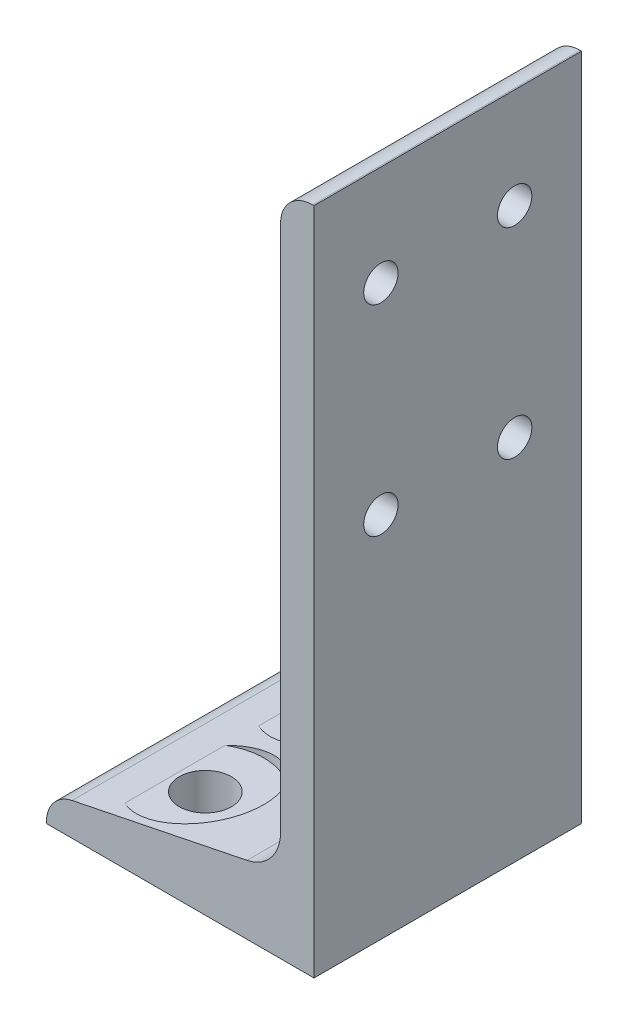
SolidWorks part; units mm, degrees
ref_plane "Front Plane" through (0, 0, 0) normal (0, 0, 1) x (1, 0, 0)
ref_plane "Top Plane" through (0, 0, 0) normal (0, 1, 0) x (1, 0, 0)
ref_plane "Right Plane" through (0, 0, 0) normal (1, 0, 0) x (0, 0, -1)
sketch "Sketch1" plane through (0, 0, 0) normal (0, 0, 1) x (1, 0, 0)
  line L0 (0, 127) -> (0, 0)
  line L1 (0, 0) -> (-50.8, 0)
  line L2 (-50.8, 0) -> (-50.8, 0.254)
  line L3 (-45.9207, 6.2273) -> (-12.7032, 12.9934)
  line L4 (-6.35, 20.7712) -> (-6.35, 120.904)
  line L5 (-0.254, 127) -> (0, 127)
  arc A0 (-12.7032, 12.9934) -> (-6.35, 20.7712) centre (-14.2875, 20.7712) ccw
  arc A1 (-50.8, 0.254) -> (-45.9207, 6.2273) centre (-44.704, 0.254) cw
  arc A2 (-6.35, 120.904) -> (-0.254, 127) centre (-0.254, 120.904) cw
  point P9 (-6.35, 14.2875)
  point P14 (-6.35, 127)
  dimension "D2" = 7.9375
  dimension "D3" = 6.096
  dimension "D1" = 14.2875
  dimension "A" = 127
  dimension "F" = 50.8
  dimension "E" = 6.35
extrude "Extrude1" add sketch "Sketch1" along normal mid plane 50.8
sketch "Sketch2" plane through (0, 0, 0) normal (1, 0, 0) x (0, 0, -1)
  line L0 (0, 0) -> (0, 69.85) construction
  line L1 (0, 69.85) -> (0, 107.95) construction
  circle A0 centre (0, 69.85) radius 3.2639
  circle A1 centre (0, 107.95) radius 3.2639
  dimension "K" = 6.5278
  dimension "B" = 69.85
  dimension "C" = 38.1
sketch "Sketch3" plane through (0, 0, 0) normal (0, 1, 0) x (1, 0, 0)
  line L0 (-50.8, 0) -> (-33.3248, 0) construction
  line L1 (-50.8, -25.4) -> (-50.8, 25.4) construction
  circle A0 centre (-33.3248, 0) radius 4.953
  dimension "L" = 9.906
  dimension "D1" = 17.4752
ref_plane "Plane1" through (0, 7.62, 0) normal (0, 1, 0) x (-1, 0, 0)
sketch "Sketch4" plane through (0, 7.62, 0) normal (0, 1, 0) x (-1, 0, 0)
  line L0 (33.3248, 11.1125) -> (50.8, 11.1125)
  line L1 (33.3248, -11.1125) -> (50.8, -11.1125)
  line L2 (50.8, 25.4) -> (50.8, -25.4) construction
  line L3 (50.8, 11.1125) -> (50.8, -11.1125)
  arc A0 (33.3248, 11.1125) -> (33.3248, -11.1125) centre (33.3248, 0) ccw
  arc A1 (33.3248, 11.1125) -> (33.3248, -11.1125) centre (33.3248, 0) cw construction
  dimension "M" = 22.225
sketch "Sketch5" [suppressed] plane through (-6.35, 0, 0) normal (-1, 0, 0) x (0, 0, 1)
  circle A0 centre (0, 69.85) radius 4.1656 construction
  circle A1 centre (0, 107.95) radius 4.1656 construction
  circle A2 centre (0, 69.85) radius 4.1656
  circle A3 centre (0, 107.95) radius 4.1656
extrude "Cut-Extrude1" [suppressed] cut sketch "Sketch5" against normal through all
sketch "Sketch6" [suppressed] plane through (0, 6.858, 0) normal (0, 1, 0) x (-1, 0, 0)
  circle A0 centre (33.3248, 0) radius 6.7437 construction
  circle A1 centre (33.3248, 0) radius 6.7437
extrude "Cut-Extrude2" [suppressed] cut sketch "Sketch6" against normal through all
sketch "Sketch7" [suppressed] plane through (0, 6.858, 0) normal (0, 1, 0) x (-1, 0, 0)
  line L3 (50.8, 14.2875) -> (33.3248, 14.2875)
  line L4 (50.8, 14.2875) -> (33.3248, 14.2875)
  line L5 (50.8, -14.2875) -> (50.8, 14.2875)
  line L6 (50.8, -14.2875) -> (50.8, 14.2875)
  line L7 (33.3248, -14.2875) -> (50.8, -14.2875)
  line L8 (33.3248, -14.2875) -> (50.8, -14.2875)
  arc A1 (33.3248, 14.2875) -> (33.3248, -14.2875) centre (33.3248, 0) ccw
  arc A2 (33.3248, 14.2875) -> (33.3248, -14.2875) centre (33.3248, 0) ccw
  dimension "D1" = 0
extrude "Cut-Extrude3" [suppressed] cut sketch "Sketch7" along normal through all
sketch "Sketch9" plane through (-6.35, 0, 0) normal (-1, 0, 0) x (0, 0, 1)
  line L0 (-12.7, 107.95) -> (12.7, 107.95) construction
  circle A0 centre (12.7, 107.95) radius 3.2639
  circle A1 centre (12.7, 69.85) radius 3.2639
  circle A2 centre (-12.7, 69.85) radius 3.2639
  circle A3 centre (-12.7, 107.95) radius 3.2639
  circle A4 centre (0, 69.85) radius 3.2639 construction
  dimension "D1" = 25.4
sketch "Sketch10" plane through (0, 0, 0) normal (0, 1, 0) x (1, 0, 0)
  line L0 (-33.3248, -12.7) -> (-33.3248, 12.7) construction
  line L1 (-50.8, -11.1125) -> (-50.8, 11.1125) construction
  line L2 (-50.8, 23.8125) -> (-33.3248, 23.8125)
  line L3 (-50.8, 23.8125) -> (-50.8, 1.5875)
  line L4 (-50.8, 1.5875) -> (-33.3248, 1.5875)
  line L6 (-50.8, -1.5875) -> (-33.3248, -1.5875)
  line L7 (-50.8, -1.5875) -> (-50.8, -23.8125)
  line L8 (-50.8, -23.8125) -> (-33.3248, -23.8125)
  circle A0 centre (-33.3248, 12.7) radius 4.953
  circle A1 centre (-33.3248, -12.7) radius 4.953
  circle A2 centre (-33.3248, 0) radius 4.953 construction
  arc A3 (-33.3248, 1.5875) -> (-33.3248, 23.8125) centre (-33.3248, 12.7) ccw
  arc A4 (-33.3248, -23.8125) -> (-33.3248, -1.5875) centre (-33.3248, -12.7) ccw
  dimension "D1" = 25.4
sketch "Sketch11" plane through (0, 7.62, 0) normal (0, 1, 0) x (-1, 0, 0)
  line L0 (33.3248, 12.7) -> (33.3248, -12.7) construction
  line L3 (33.3248, -23.8125) -> (50.8, -23.8125)
  line L4 (50.8, -1.5875) -> (33.3248, -1.5875)
  line L5 (50.8, -23.8125) -> (50.8, -1.5875)
  line L6 (33.3248, -23.8125) -> (50.8, -23.8125) construction
  line L7 (50.8, -1.5875) -> (33.3248, -1.5875) construction
  line L8 (50.8, -23.8125) -> (50.8, -1.5875) construction
  line L9 (33.3248, 1.5875) -> (50.8, 1.5875)
  line L10 (50.8, 1.5875) -> (50.8, 23.8125)
  line L11 (50.8, 23.8125) -> (33.3248, 23.8125)
  line L12 (33.3248, 1.5875) -> (50.8, 1.5875) construction
  line L13 (50.8, 1.5875) -> (50.8, 23.8125) construction
  line L14 (50.8, 23.8125) -> (33.3248, 23.8125) construction
  arc A5 (33.3248, -1.5875) -> (33.3248, -23.8125) centre (33.3248, -12.7) ccw
  circle A6 centre (33.3248, -12.7) radius 11.1125
  arc A7 (33.3248, 23.8125) -> (33.3248, 1.5875) centre (33.3248, 12.7) ccw
  circle A8 centre (33.3248, 12.7) radius 11.1125
  dimension "D3" = 0
  dimension "D4" = 0
extrude "Cut-Extrude4" cut sketch "Sketch11" along normal through all
sketch "Sketch12" plane through (0, 7.62, 0) normal (0, 1, 0) x (-1, 0, 0)
  circle A0 centre (33.3248, 12.7) radius 4.953 construction
  circle A1 centre (33.3248, -12.7) radius 4.953 construction
  circle A2 centre (33.3248, 12.7) radius 4.953
  circle A3 centre (33.3248, -12.7) radius 4.953
extrude "Cut-Extrude5" cut sketch "Sketch12" against normal through all
sketch "Sketch13" plane through (-6.35, 0, 0) normal (-1, 0, 0) x (0, 0, 1)
  circle A0 centre (-12.7, 69.85) radius 3.2639 construction
  circle A1 centre (-12.7, 107.95) radius 3.2639 construction
  circle A2 centre (12.7, 107.95) radius 3.2639 construction
  circle A3 centre (12.7, 69.85) radius 3.2639 construction
  circle A4 centre (-12.7, 69.85) radius 3.2639
  circle A5 centre (-12.7, 107.95) radius 3.2639
  circle A6 centre (12.7, 107.95) radius 3.2639
  circle A7 centre (12.7, 69.85) radius 3.2639
extrude "Cut-Extrude6" cut sketch "Sketch13" against normal through all
equation "\"D1@Sketch9\" = \"J@Extrude1\"/2"
equation "\"D1@Sketch10\" = \"J@Extrude1\"/2"
